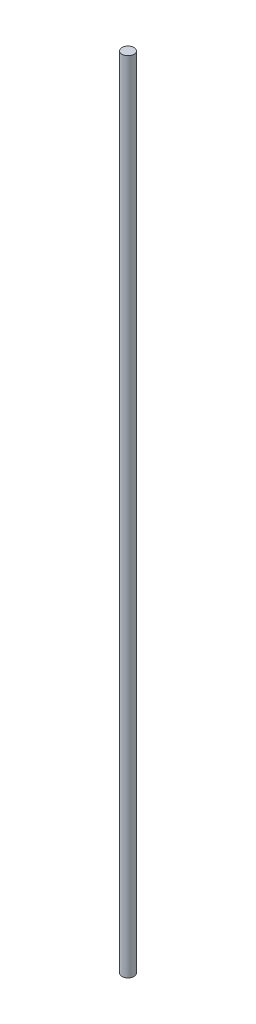
SolidWorks part; units mm, degrees
ref_plane "Front Plane" through (0, 0, 0) normal (0, 0, 1) x (1, 0, 0)
ref_plane "Top Plane" through (0, 0, 0) normal (0, 1, 0) x (1, 0, 0)
ref_plane "Right Plane" through (0, 0, 0) normal (1, 0, 0) x (0, 0, -1)
sketch "Sketch2" plane through (0, 0, 0) normal (0, 1, 0) x (1, 0, 0)
  circle A0 centre (0, 0) radius 3.1
extrude "Boss-Extrude1" add sketch "Sketch2" along normal blind 415
